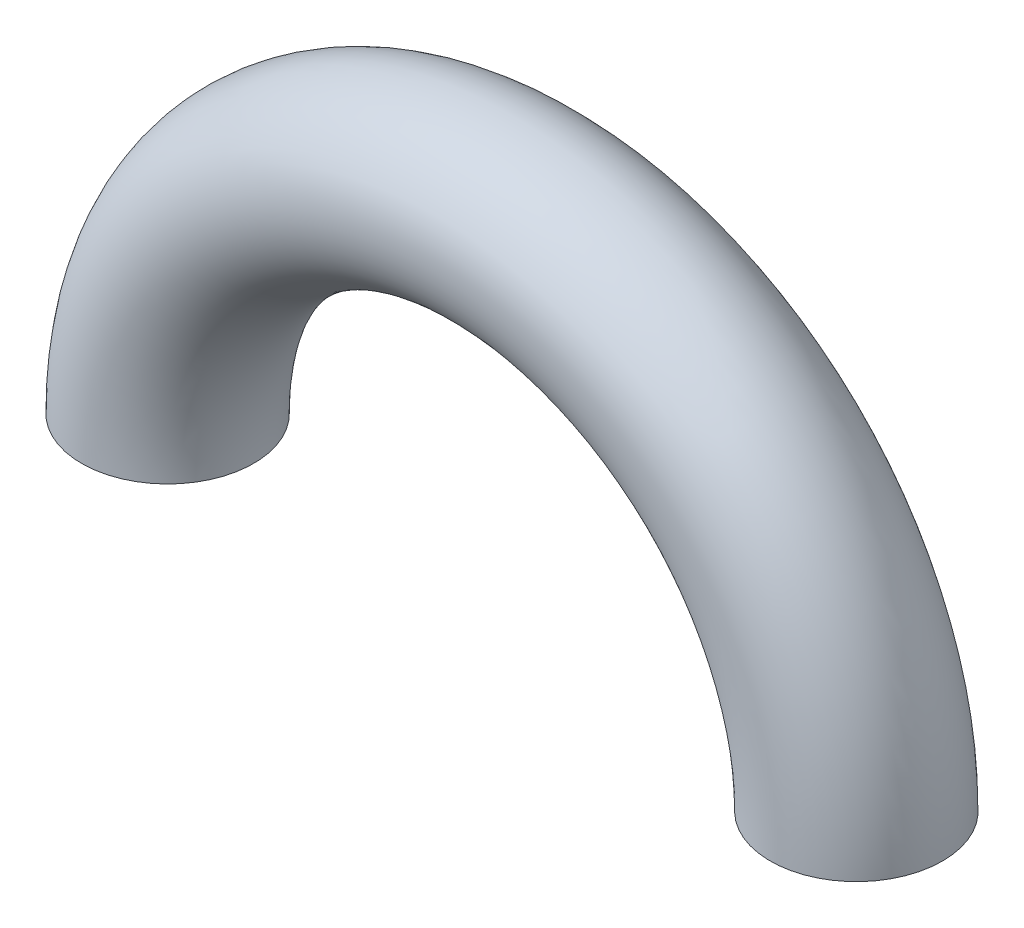
SolidWorks part; units mm, degrees
material "AISI 304"
ref_plane "Front Plane" through (0, 0, 0) normal (0, 0, 1) x (1, 0, 0)
ref_plane "Top Plane" through (0, 0, 0) normal (0, 1, 0) x (1, 0, 0)
ref_plane "Right Plane" through (0, 0, 0) normal (1, 0, 0) x (0, 0, -1)
sketch "Sketch2" plane through (0, 0, 0) normal (0, 1, 0) x (1, 0, 0)
  circle A0 centre (0, 0) radius 2.5
  dimension "D1" = 5
sketch "Sketch3" plane through (0, 0, 0) normal (0, 0, 1) x (1, 0, 0)
  arc A1 (20, 0) -> (0, 0) centre (10, 0) ccw
sweep "Sweep1" add profiles "Sketch2" path "Sketch3"
